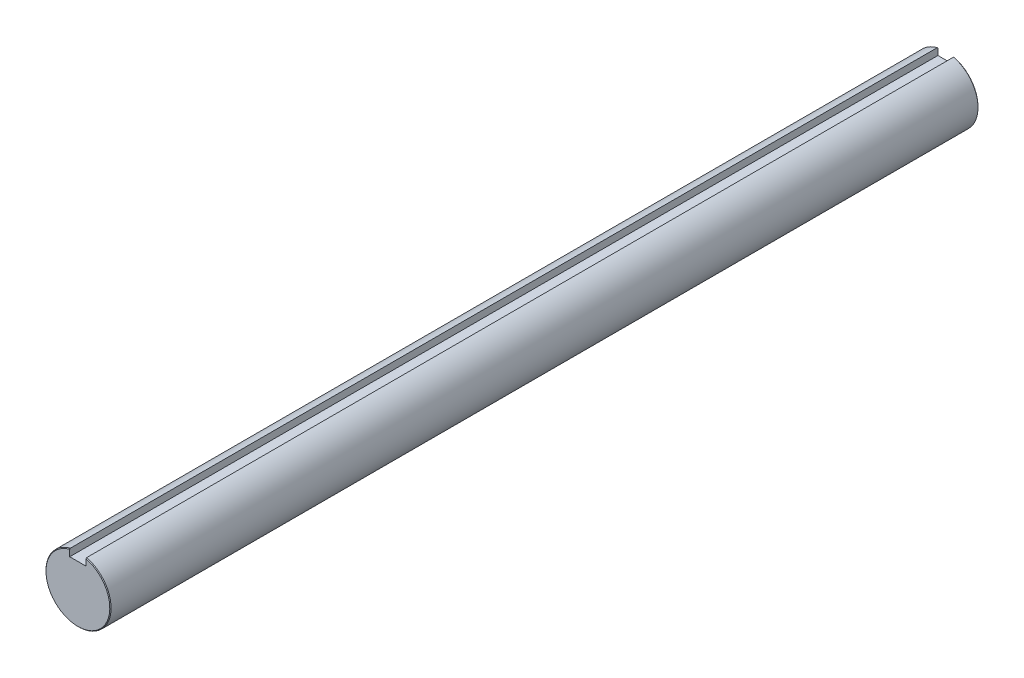
SolidWorks part; units mm, degrees
ref_plane "Front Plane" through (0, 0, 0) normal (0, 0, 1) x (1, 0, 0)
ref_plane "Top Plane" through (0, 0, 0) normal (0, 1, 0) x (1, 0, 0)
ref_plane "Right Plane" through (0, 0, 0) normal (1, 0, 0) x (0, 0, -1)
sketch "Sketch1" plane through (0, 0, 0) normal (1, 0, 0) x (0, 0, -1)
  line L0 (0, 0) -> (0, 9.525) construction
  line L1 (-127, 9.525) -> (127, 9.525)
  line L2 (-127, 9.525) -> (-127, -9.525)
  line L3 (-127, -9.525) -> (127, -9.525)
  line L4 (127, 9.525) -> (127, -9.525)
  line L5 (-127, 9.525) -> (127, -9.525) construction
  line L6 (-127, -9.525) -> (127, 9.525) construction
  line L7 (0, 0) -> (0, -9.525) construction
  point P0 (0, 0)
  point P8 (-105.0925, 9.525)
  point P10 (105.0925, 9.525)
  point P11 (-97.79, -9.525)
  point P12 (101.7035, -9.525)
  dimension "Diameter" = 19.05
  dimension "Length" = 254
  dimension "D1" = 21.9075
  dimension "D2" = 21.9075
  dimension "D3" = 29.21
  dimension "D4" = 25.2965
  dimension "Keyway Length" = 254
sketch "Sketch2" plane through (0, 0, 0) normal (0, 0, 1) x (1, 0, 0)
  line L0 (0, 0) -> (0, 9.525) construction
  line L2 (2.3876, 7.1374) -> (-2.3876, 7.1374)
  line L3 (2.3876, 7.1374) -> (2.3876, 9.525)
  line L4 (2.3876, 9.525) -> (-2.3876, 9.525)
  line L5 (-2.3876, 7.1374) -> (-2.3876, 9.525)
  line L6 (2.3876, 7.1374) -> (-2.3876, 9.525) construction
  line L7 (2.3876, 9.525) -> (-2.3876, 7.1374) construction
  circle A0 centre (0, 0) radius 9.525
  point P3 (0, 8.3312)
  point P10 (0, -9.525)
  dimension "D1" = 16.6624
  dimension "Keyway Width" = 4.7752
  dimension "Keyway Depth" = 2.3876
sketch "Sketch3" plane through (0, 0, 0) normal (0, 0, 1) x (1, 0, 0)
  line L1 (-2.3876, 7.1374) -> (-2.3876, 9.525) construction
  line L2 (2.3876, 7.1374) -> (-2.3876, 7.1374) construction
  line L3 (2.3876, 7.1374) -> (2.3876, 9.525) construction
  line L5 (-2.3876, 7.1374) -> (-2.3876, 9.2209)
  line L6 (2.3876, 7.1374) -> (-2.3876, 7.1374)
  line L7 (2.3876, 7.1374) -> (2.3876, 9.2209)
  arc A1 (-2.3876, 9.2209) -> (2.3876, 9.2209) centre (0, 0) ccw
  circle A2 centre (0, 0) radius 9.525 construction
extrude "Boss-Extrude1" add sketch "Sketch3" along normal up to vertex (127 mm away) and the other way up to vertex (127 mm away) up to point (0, 9.525, 127) other way up to point (0, 9.525, -127)
chamfer "Chamfer1" distance 0.1905 angle 45 2 edges at (0, -9.525, 127) (0, -9.525, -127)
equation "\"D2@Sketch1\"=1.15*\"Diameter@Sketch1\""
equation "\"D1@Sketch1\"=\"D2@Sketch1\""
equation "\"D3@Sketch1\"=\"D2@Sketch1\"*4/3"
equation "\"D4@Sketch1\"=\"D2@Sketch1\"/(tan(.5236*180/pi)*2)*4/3"
equation "\"D1@Chamfer1\"=\"Diameter@Sketch1\"*.01"
